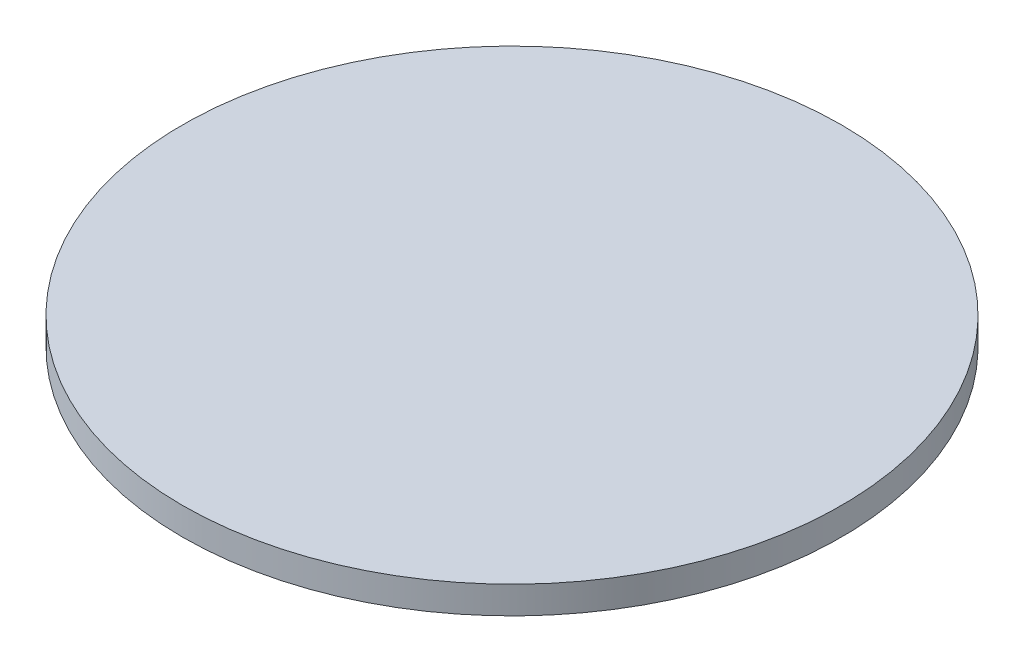
SolidWorks part; units mm, degrees
material "AISI 1020"
ref_plane "Front Plane" through (0, 0, 0) normal (0, 0, 1) x (1, 0, 0)
ref_plane "Top Plane" through (0, 0, 0) normal (0, 1, 0) x (1, 0, 0)
ref_plane "Right Plane" through (0, 0, 0) normal (1, 0, 0) x (0, 0, -1)
sketch "Sketch2" plane through (0, 0, 0) normal (0, 1, 0) x (1, 0, 0)
  circle A0 centre (0, 0) radius 152.4
  dimension "D1" = 304.8
extrude "Boss-Extrude1" add sketch "Sketch2" along normal blind 12.7
